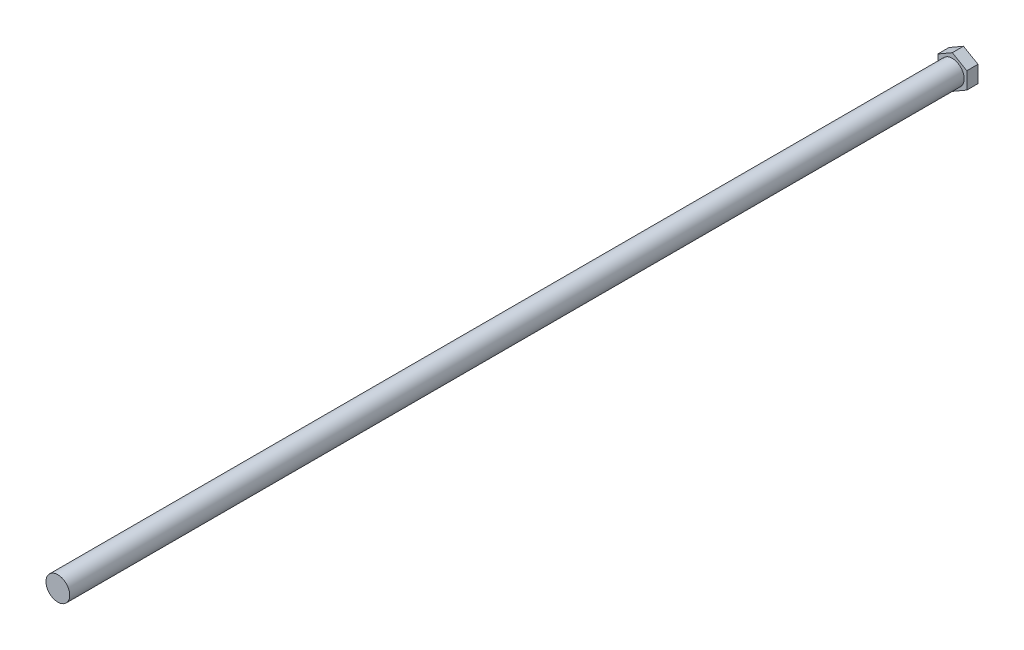
SolidWorks part; units mm, degrees
ref_plane "Front Plane" through (0, 0, 0) normal (0, 0, 1) x (1, 0, 0)
ref_plane "Top Plane" through (0, 0, 0) normal (0, 1, 0) x (1, 0, 0)
ref_plane "Right Plane" through (0, 0, 0) normal (1, 0, 0) x (0, 0, -1)
sketch "Sketch2" plane through (0, 0, 0) normal (0, 0, 1) x (1, 0, 0)
  circle A0 centre (0, 0) radius 2.125
  dimension "D1" = 4.25
extrude "Boss-Extrude1" add sketch "Sketch2" along normal blind 160
sketch "Sketch3" plane through (0, 0, 0) normal (0, 0, -1) x (-1, 0, 0)
  line L1 (0, 3) -> (-2.5981, 1.5)
  line L2 (-2.5981, 1.5) -> (-2.5981, -1.5)
  line L3 (-2.5981, -1.5) -> (0, -3)
  line L4 (0, -3) -> (2.5981, -1.5)
  line L5 (2.5981, -1.5) -> (2.5981, 1.5)
  line L6 (2.5981, 1.5) -> (0, 3)
  circle A0 centre (0, 0) radius 2.5981 construction
  dimension "D1" = 3
extrude "Boss-Extrude2" add sketch "Sketch3" along normal blind 2
